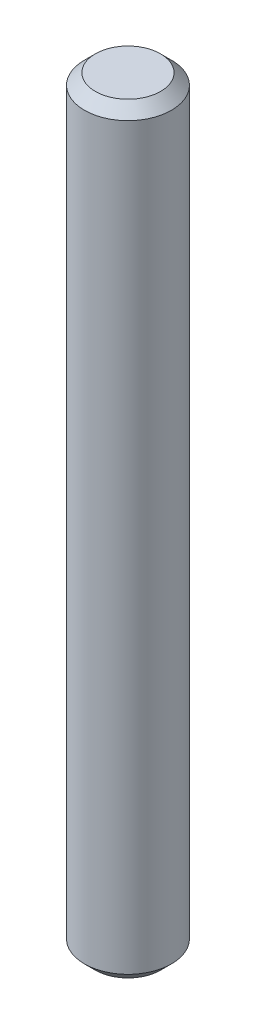
SolidWorks part; units mm, degrees
ref_plane "前基準面" through (0, 0, 0) normal (0, 0, 1) x (1, 0, 0)
ref_plane "上基準面" through (0, 0, 0) normal (0, 1, 0) x (1, 0, 0)
ref_plane "右基準面" through (0, 0, 0) normal (1, 0, 0) x (0, 0, -1)
sketch "草圖1" plane through (0, 0, 0) normal (0, 1, 0) x (1, 0, 0)
  circle A0 centre (0, 0) radius 4
  dimension "D1" = 8
extrude "填料-伸長1" add sketch "草圖1" along normal blind 70
chamfer "導角1" distance 1 angle 45 2 edges at (0, 0, 4) (0, 70, 4)
